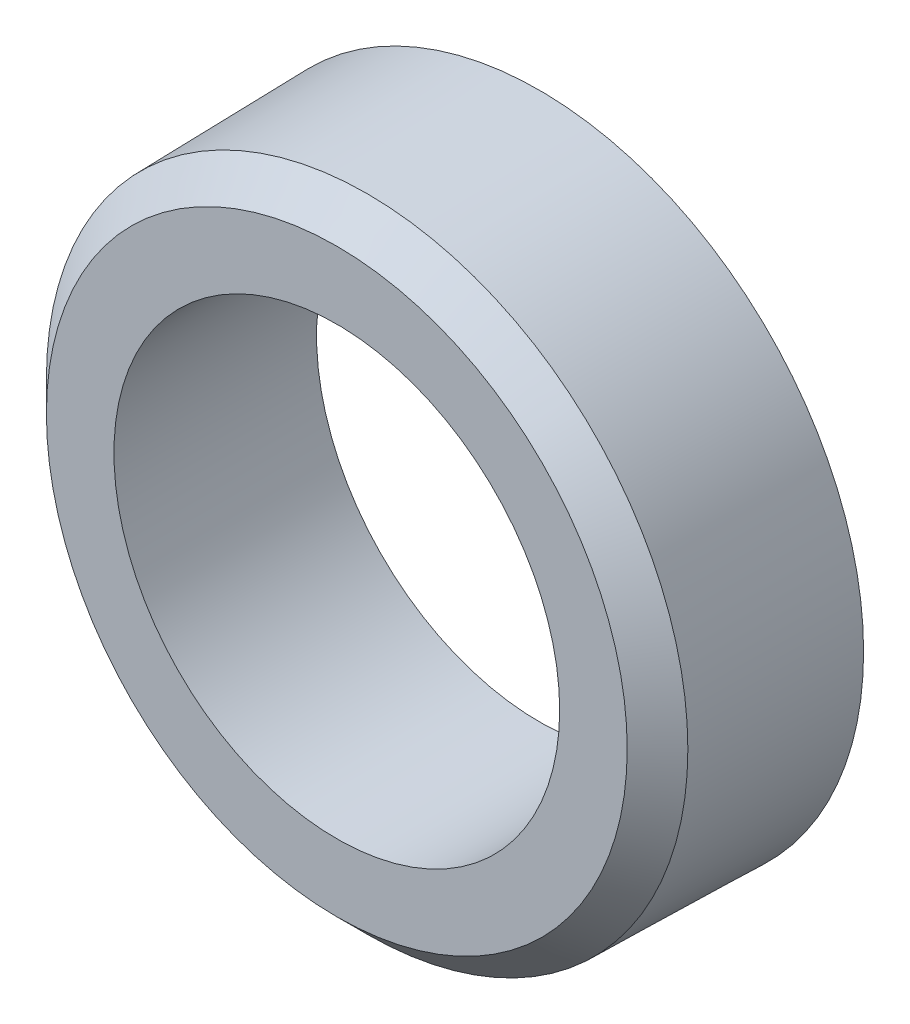
SolidWorks part; units mm, degrees
ref_plane "Спереди" through (0, 0, 0) normal (0, 0, 1) x (1, 0, 0)
ref_plane "Сверху" through (0, 0, 0) normal (0, 1, 0) x (1, 0, 0)
ref_plane "Справа" through (0, 0, 0) normal (1, 0, 0) x (0, 0, -1)
sketch "Эскиз1" plane through (0, 0, 0) normal (0, 0, 1) x (1, 0, 0)
  circle A0 centre (0, 0) radius 9.6
  circle A1 centre (0, 0) radius 6.6
  dimension "D1" = 3
  dimension "D2" = 19.2
extrude "Вытянуть1" add sketch "Эскиз1" along normal blind 6
ref_axis "Ось1" through (0, 0, 6) along (0, 0, -1)
chamfer "Фаска1" distance 1 angle 45 1 edges at (9.6, 0, 6)
sketch "Эскиз4" plane through (0, 0, 0) normal (1, 0, 0) x (0, 0, -1)
  line L0 (0, 9.6) -> (-6, 9.48)
  line L2 (-6, 9.48) -> (-6, 9.6)
  line L3 (-6, 9.6) -> (0, 9.6)
  line L5 (-6, 8.6) -> (-6, -8.6) construction
  line L6 (-5, 9.6) -> (-5, 9.5) construction
  line L7 (-5, -9.6) -> (-5, 9.6) construction
  line L8 (-6, 0) -> (0, 0) construction
  dimension "D1" = 9.5
revolve "Вырез-Повернуть1" cut sketch "Эскиз4" angle 360 about axis through (0, 0, 6) along (0, 0, -1)
